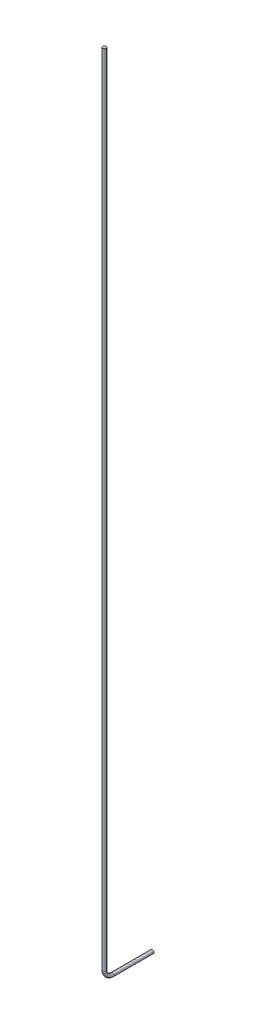
SolidWorks part; units mm, degrees
ref_plane "正面" through (0, 0, 0) normal (0, 0, 1) x (1, 0, 0)
ref_plane "平面" through (0, 0, 0) normal (0, 1, 0) x (1, 0, 0)
ref_plane "右側面" through (0, 0, 0) normal (1, 0, 0) x (0, 0, -1)
sketch "ｽｹｯﾁ1" plane through (0, 0, 0) normal (0, 0, 1) x (1, 0, 0)
  circle A0 centre (0, 0) radius 1.06
  dimension "D1" = 2.12
extrude "ﾎﾞｽ - 押し出し1" add sketch "ｽｹｯﾁ1" along normal blind 20
sketch "ｽｹｯﾁ2" plane through (0, 0, 20) normal (0, 0, 1) x (1, 0, 0)
  circle A1 centre (0, 0) radius 1.06
  circle A2 centre (0, 0) radius 1.06
  dimension "D1" = 0
sketch "ｽｹｯﾁ3" plane through (0, 0, 0) normal (1, 0, 0) x (0, 0, -1)
  line L0 (-20, 0) -> (-25, 0)
  line L1 (-20, 1.06) -> (-20, -1.06) construction
  line L2 (-30, 5) -> (-30, 505)
  line L3 (-20, 1.06) -> (-20, -1.06) construction
  arc A0 (-25, 0) -> (-30, 5) centre (-25, 5) cw
  point P8 (-30, 0)
  dimension "D2" = 5
  dimension "D1" = 10
  dimension "D3" = 500
sweep "ｽｲｰﾌﾟ1" add profiles "ｽｹｯﾁ2" path "ｽｹｯﾁ3"
